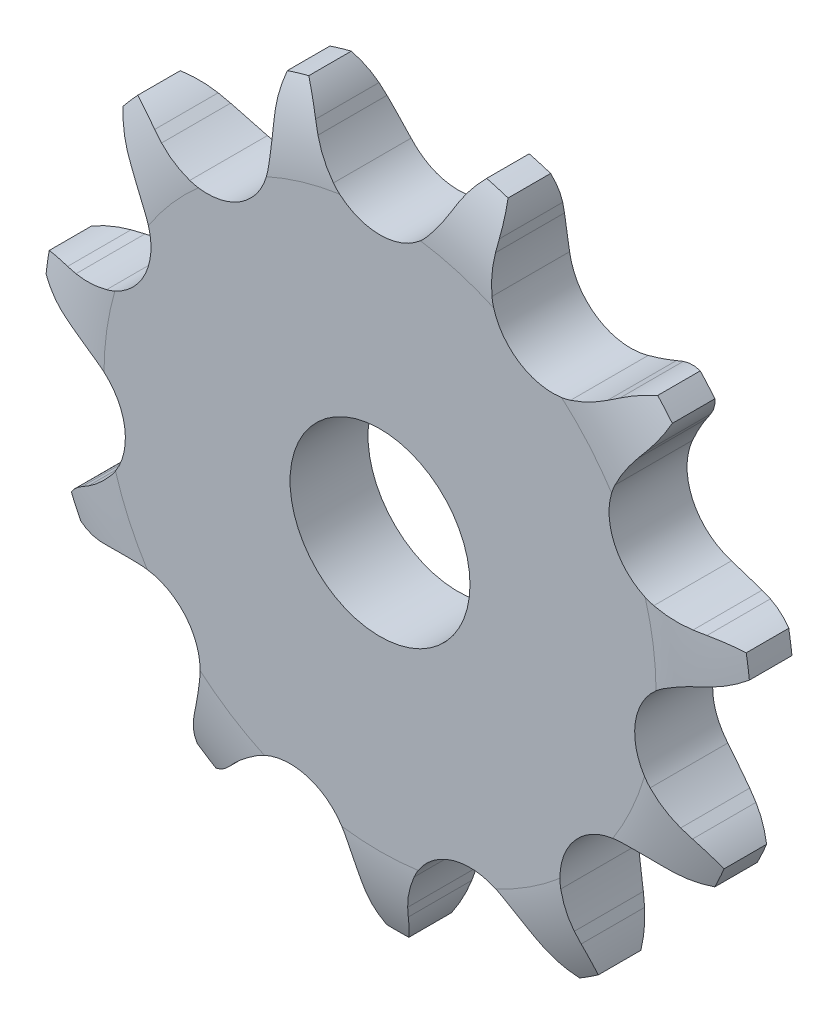
SolidWorks part; units mm, degrees
ref_plane "Front Plane" through (0, 0, 0) normal (0, 0, 1) x (1, 0, 0)
ref_plane "Top Plane" through (0, 0, 0) normal (0, 1, 0) x (1, 0, 0)
ref_plane "Right Plane" through (0, 0, 0) normal (1, 0, 0) x (0, 0, -1)
sketch "Sketch0" plane through (0, 0, 0) normal (0, 0, 1) x (1, 0, 0)
  line L0 (3, -10.2171) -> (0, 0) construction
  line L1 (0, 0) -> (8.0475, -6.9732) construction
  line L2 (0, 0) -> (-3, -10.2171) construction
  line L3 (3, -10.2171) -> (8.0475, -6.9732) construction
  line L4 (3, -10.2171) -> (-3, -10.2171) construction
  line L5 (5.2869, -9.523) -> (5.0296, -9.2556)
  line L6 (3, -10.2171) -> (0, -11.0979) construction
  line L7 (0.7008, -10.8696) -> (0.7728, -10.5055)
  line L8 (0, -10.2171) -> (0, -12.0171) construction
  line L9 (4.1209, -8.5029) -> (1.2486, -12.8953) construction
  line L10 (0, 0) -> (0, -10.2171) construction
  line L11 (5.0296, -9.2556) -> (1.2486, -12.8953) construction
  line L12 (0, -12.0171) -> (0, -12.3528) construction
  line L13 (7.711, -7.1895) -> (5.2869, -9.523) construction
  circle A0 centre (0, 0) radius 12.0171 construction
  circle A1 centre (0, 0) radius 10.6484 construction
  arc A2 (-3.4298, -13.4779) -> (10.172, -9.484) centre (0, 0) ccw
  circle A3 centre (0, 0) radius 12.3528 construction
  circle A4 centre (3, -10.2171) radius 2 construction
  arc A7 (4.1209, -8.5029) -> (1.1303, -9.3811) centre (3, -10.2171) ccw
  circle A8 centre (3, -10.2171) radius 2.0481 construction
  arc A9 (5.2869, -9.523) -> (10.172, -9.484) centre (7.711, -7.1895) ccw
  arc A10 (5.0296, -9.2556) -> (4.1209, -8.5029) centre (1.2486, -12.8953) ccw
  arc A11 (0.7008, -10.8696) -> (-3.4298, -13.4779) centre (-2.6, -10.2171) cw
  arc A12 (0.7728, -10.5055) -> (1.1303, -9.3811) centre (5.9213, -11.5233) cw
  dimension "D1" = 2.0481
  dimension "R" = 2.0481
sketch "Sketch1" plane through (0, 0, 0) normal (1, 0, 0) x (0, 0, -1)
  line L0 (1.3, 0) -> (-1.3, 0)
  line L1 (-1.3, 0) -> (-1.3, 9.2046)
  line L2 (-1.3, 10.6484) -> (0, 10.6484) construction
  line L3 (-0.6, 12.0171) -> (0.6, 12.0171)
  line L5 (1.3, 9.2046) -> (1.3, 0)
  line L7 (0, 12.0171) -> (0, 0) construction
  line L8 (-1.3, 9.2046) -> (1.3, 9.2046) construction
  line L9 (0, 12.0171) -> (0, -12.0171) construction
  line L10 (-1.3, 9.2046) -> (-1.3, 12.0171) construction
  line L11 (-1.3, 12.0171) -> (-0.6, 12.0171) construction
  line L12 (0.6, 12.0171) -> (1.3, 12.0171) construction
  line L13 (1.3, 12.0171) -> (1.3, 9.2046) construction
  line L14 (0, 0) -> (-6.4008, 0) construction
  line L15 (-1.3, 10.6484) -> (-1.3, 6.5484) construction
  line L22 (1.3, 0) -> (-8.7, 0) construction
  line L24 (-1.3, 0) -> (-1.3, 6.5484) construction
  arc A0 (-0.6, 12.0171) -> (-1.3, 9.2046) centre (4.7, 9.2046) ccw
  arc A1 (0.6, 12.0171) -> (1.3, 9.2046) centre (-4.7, 9.2046) cw
  dimension "R" = 6
revolve "Revolve1" add sketch "Sketch1" angle 360 mid plane about L0
extrude "Cut-Extrude1" cut sketch "Sketch0" against normal through all and the other way through all
pattern_circular "CirPattern1" count 11 over 360 about axis through (0, 0, 0) along (0, 0, 1) of "Cut-Extrude1"
sketch "Sketch2" plane through (0, 0, 0) normal (0, 0, 1) x (1, 0, 0)
  circle A0 centre (0, 0) radius 3 construction
  circle A1 centre (0, 0) radius 7
  circle A2 centre (0, 0) radius 11.8 construction
  dimension "Bore" = 6
  dimension "Hub Dia." = 14
  dimension "OD" = 23.6
extrude "Boss-Extrude1" add sketch "Sketch2" along normal up to vertex (8.7 mm away) from surface at 1.3 starting at face at (0, 0, 1.3)
sketch "Sketch3" plane through (0, 0, 0) normal (0, 0, 1) x (1, 0, 0)
  circle A0 centre (0, 0) radius 3 construction
  circle A1 centre (0, 0) radius 3
extrude "Cut-Extrude2" cut sketch "Sketch3" along normal through all and the other way through all
sketch "Sketch4" plane through (0, 0, 0) normal (1, 0, 0) x (0, 0, -1)
  line L0 (-8.7, 7) -> (-8.7, 6.5)
  line L1 (-1.3, 12.0171) -> (-3.25, 12.0171)
  line L2 (-1.3, 12.0171) -> (-1.3, 6.5484)
  line L3 (-1.3, 6.5484) -> (-3.25, 6.5484)
  line L4 (-3.25, 12.0171) -> (-3.25, 6.5484)
  line L9 (-8.7, 6.5) -> (-8.2, 7)
  line L10 (-8.2, 7) -> (-8.7, 7)
  dimension "C" = 0.5
  dimension "D3" = 1.95
revolve "Cut-Revolve1" cut sketch "Sketch4" angle 360 mid plane about L22
sketch "Sketch5" plane through (0, 0, 0) normal (0, 0, 1) x (1, 0, 0)
  circle A0 centre (0, 0) radius 11.8 construction
  circle A1 centre (0, 0) radius 11.8
extrude "Cut-Extrude3" cut sketch "Sketch5" against normal through all and the other way through all flip side to cut
sketch "Sketch6" plane through (0, 0, 1.3) normal (0, 0, 1) x (1, 0, 0)
  circle A0 centre (0, 0) radius 8.0846
extrude "Cut-Extrude4" cut sketch "Sketch6" along normal blind 10
equation "\"360/N@Sketch0\" = 360/\"Teeth@CirPattern1\""
equation "\"Ds@Sketch0\" = 1.005 * \"Dr@Sketch0\" + ( 0.003 * 25.4 ) "
equation "\"R@Sketch0\" = 1/2 * \"Ds@Sketch0\""
equation "\"A@Sketch0\" = 35 +  ( 60 / \"Teeth@CirPattern1\" ) "
equation "\"B@Sketch0\" = 18 -  ( 56 / \"Teeth@CirPattern1\" )"
equation "\"ac@Sketch0\" = 0.8 * \"Dr@Sketch0\""
equation "\"ab@Sketch0\" = 1.4 * \"Dr@Sketch0\""
equation "\"J@Sketch0\" = 0.3 * \"Pitch@Sketch0\""
equation "\"D3@Sketch4\" = \"t@Sketch1\" * 3 / 4"
